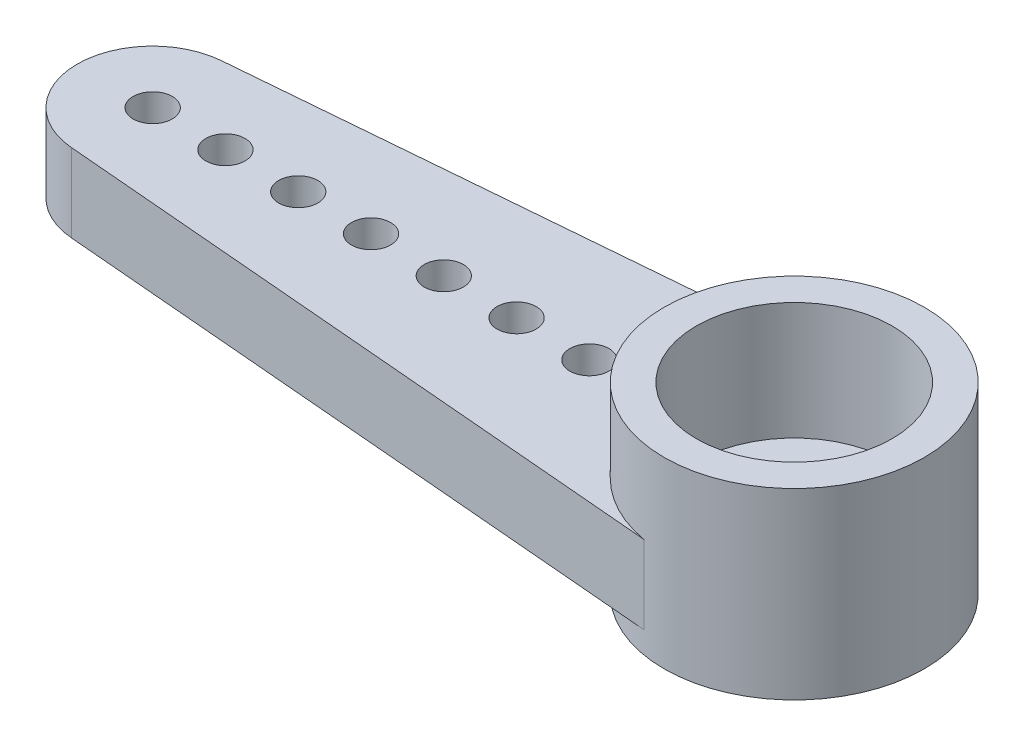
SolidWorks part; units mm, degrees
ref_plane "前视基准面" through (0, 0, 0) normal (0, 0, 1) x (1, 0, 0)
ref_plane "上视基准面" through (0, 0, 0) normal (0, 1, 0) x (1, 0, 0)
ref_plane "右视基准面" through (0, 0, 0) normal (1, 0, 0) x (0, 0, -1)
sketch "草图1" plane through (0, 0, 0) normal (0, 1, 0) x (1, 0, 0)
  circle A0 centre (0, 0) radius 3.325
  dimension "D1" = 6.65
extrude "凸台-拉伸1" add sketch "草图1" along normal mid plane 4.68
sketch "草图2" plane through (0, 2.34, 0) normal (0, 1, 0) x (1, 0, 0)
  circle A0 centre (0, 0) radius 2.5
  dimension "D1" = 5
extrude "切除-拉伸1" cut sketch "草图2" against normal blind 3 contours A0
sketch "草图3" plane through (0, -0.66, 0) normal (0, 1, 0) x (1, 0, 0)
  circle A0 centre (0, 0) radius 1
  dimension "D1" = 2
extrude "切除-拉伸2" cut sketch "草图3" against normal through all
ref_plane "基准面1" through (0, -2.39, 0) normal (0, 1, 0) x (1, 0, 0)
ref_plane "基准面2" through (0, 0.22, 0) normal (0, -1, 0) x (-1, 0, 0)
sketch "草图4" plane through (0, 0.22, 0) normal (0, -1, 0) x (-1, 0, 0)
  line L0 (0, 3.325) -> (0, -3.325) construction
  line L1 (-3.325, 0) -> (18.325, 0) construction
  line L2 (16.55, 1.92) -> (16.55, -1.92) construction
  line L3 (0, 3.325) -> (16.55, 1.92)
  line L4 (0, -3.325) -> (16.55, -1.92)
  circle A0 centre (0, 0) radius 3.325 construction
  arc A1 (16.55, 1.92) -> (16.55, -1.92) centre (16.3991, 0) cw
  arc A3 (0, 3.325) -> (0, -3.325) centre (-0.871, 0) cw
  point P9 (0, 0)
  point P13 (16.55, 0)
  point P17 (16.55, 0)
  dimension "D1" = 21.65
  dimension "D2" = 16.55
  dimension "D3" = 3.84
extrude "凸台-拉伸2" add sketch "草图4" along normal blind 2
sketch "草图5" plane through (0, -1.78, 0) normal (0, -1, 0) x (-1, 0, 0)
  line L0 (18.325, 0) -> (-49981.675, 0) construction
  arc A0 (16.55, -1.92) -> (16.55, 1.92) centre (16.3991, 0) ccw construction
  circle A3 centre (14.535, 0) radius 0.5
  circle A4 centre (0, 0) radius 1 construction
  circle A5 centre (16.395, 0) radius 0.5
  circle A7 centre (12.675, 0) radius 0.5
  circle A8 centre (10.815, 0) radius 0.5
  circle A9 centre (8.955, 0) radius 0.5
  circle A10 centre (7.095, 0) radius 0.5
  circle A11 centre (5.235, 0) radius 0.5
  circle A12 centre (0, 0) radius 3.325 construction
  point P5 (18.325, 0)
  point P9 (5.235, 0)
  point P10 (1, 0)
  point P17 (14.535, 0)
  point P18 (12.675, 0)
  point P19 (10.815, 0)
  point P20 (8.955, 0)
  point P29 (7.095, 0)
  point P31 (14.035, 0)
  point P32 (-3.325, 0)
  dimension "D2" = 1.86
  dimension "D5" = 1
  dimension "D6" = 1
  dimension "D7" = 1
  dimension "D11" = 1
  dimension "D13" = 1
  dimension "D14" = 1
  dimension "D15" = 1
  dimension "D4" = 1.86
  dimension "D8" = 1.86
  dimension "D9" = 1.86
  dimension "D10" = 1.86
  dimension "D12" = 1.86
  dimension "D16" = 17.36
extrude "切除-拉伸3" cut sketch "草图5" against normal blind 10
